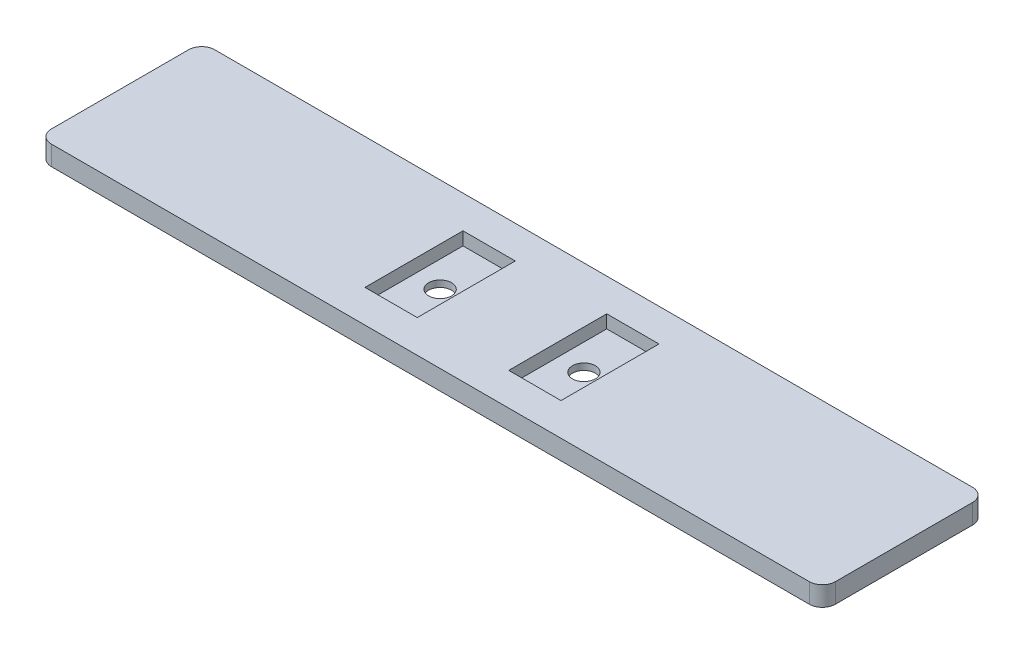
SolidWorks part; units mm, degrees
ref_plane "Front Plane" through (0, 0, 0) normal (0, 0, 1) x (1, 0, 0)
ref_plane "Top Plane" through (0, 0, 0) normal (0, 1, 0) x (1, 0, 0)
ref_plane "Right Plane" through (0, 0, 0) normal (1, 0, 0) x (0, 0, -1)
sketch "Top Cover" plane through (0, 0, 0) normal (0, 1, 0) x (1, 0, 0)
  line L1 (60, -12.5) -> (-60, -12.5)
  line L2 (60, -12.5) -> (60, 12.5)
  line L3 (60, 12.5) -> (-60, 12.5)
  line L4 (-60, -12.5) -> (-60, 12.5)
  line L5 (60, -12.5) -> (-60, 12.5) construction
  line L6 (60, 12.5) -> (-60, -12.5) construction
  point P0 (0, 0)
  dimension "D1" = 25
  dimension "D2" = 120
extrude "Boss-Extrude1" add sketch "Top Cover" along normal blind 3
sketch "Attachment Point" plane through (0, 3, 0) normal (0, 1, 0) x (1, 0, 0)
  line L0 (-60, 0) -> (60, 0) construction
  line L1 (-15, 7.5) -> (-7, 7.5)
  line L2 (-15, 7.5) -> (-15, -7.5)
  line L3 (-15, -7.5) -> (-7, -7.5)
  line L4 (-7, 7.5) -> (-7, -7.5)
  line L5 (-15, 7.5) -> (-7, -7.5) construction
  line L6 (-15, -7.5) -> (-7, 7.5) construction
  line L7 (-60, 12.5) -> (-60, -12.5) construction
  line L8 (60, -12.5) -> (60, 12.5) construction
  line L9 (0, -12.5) -> (0, -7.5) construction
  line L10 (-60, -12.5) -> (60, -12.5) construction
  line L11 (15, -7.5) -> (7, 7.5) construction
  line L12 (15, 7.5) -> (7, -7.5) construction
  line L13 (7, 7.5) -> (7, -7.5)
  line L14 (15, -7.5) -> (7, -7.5)
  line L15 (15, 7.5) -> (15, -7.5)
  line L16 (15, 7.5) -> (7, 7.5)
  point P0 (-11, 0)
  dimension "D1" = 11
  dimension "D2" = 8
  dimension "D3" = 15
extrude "Cut-Extrude1" cut sketch "Attachment Point" against normal blind 2
sketch "Sketch4" plane through (0, 3, 0) normal (0, 1, 0) x (1, 0, 0)
  line L0 (0, -12.5) -> (0, -3.0256) construction
  line L1 (-60, -12.5) -> (60, -12.5) construction
  line L2 (-60, 0) -> (-44.806, 0) construction
  line L3 (-60, 12.5) -> (-60, -12.5) construction
  line L4 (-11, 7.5) -> (-11, -7.5) construction
  line L5 (-7, 7.5) -> (-15, 7.5) construction
  line L6 (-15, -7.5) -> (-7, -7.5) construction
  circle A0 centre (-11, 0) radius 1.75
  circle A1 centre (11, 0) radius 1.75
  dimension "D1" = 3.5
extrude "M3 Screw CUT" cut sketch "Sketch4" against normal through all
fillet "Fillet1" radius 2 1 edges at (-60, 1.5, 12.5)
fillet "Fillet2" radius 2 1 edges at (60, 1.5, 12.5)
fillet "Fillet3" radius 2 1 edges at (60, 1.5, -12.5)
fillet "Fillet4" radius 2 1 edges at (-60, 1.5, -12.5)
